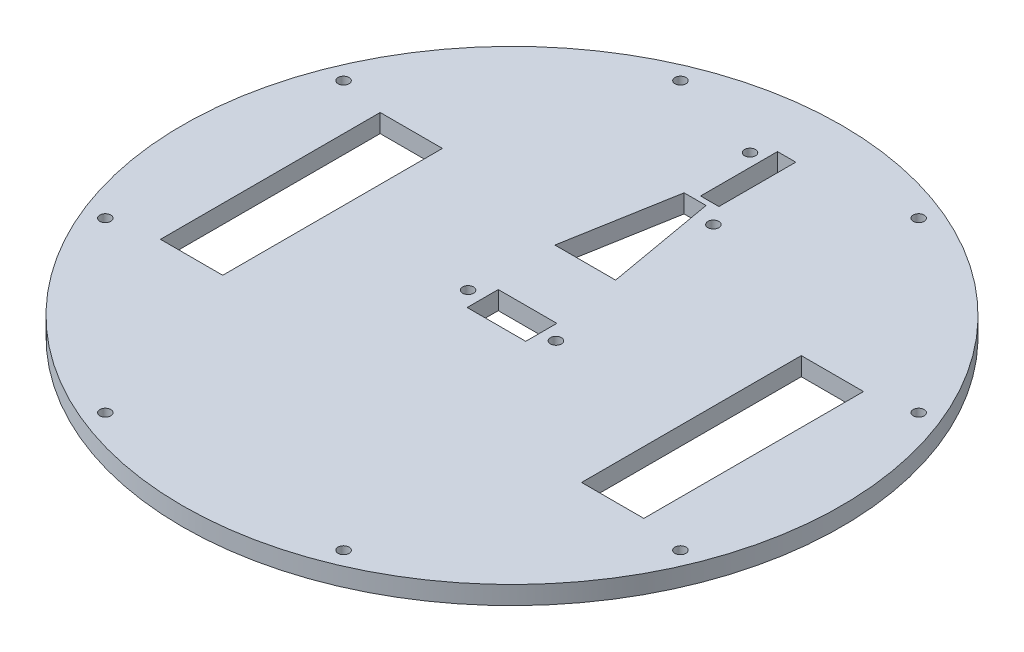
SolidWorks part; units mm, degrees
ref_plane "Front Plane" through (0, 0, 0) normal (0, 0, 1) x (1, 0, 0)
ref_plane "Top Plane" through (0, 0, 0) normal (0, 1, 0) x (1, 0, 0)
ref_plane "Right Plane" through (0, 0, 0) normal (1, 0, 0) x (0, 0, -1)
sketch "Sketch1" plane through (0, 0, 0) normal (0, 1, 0) x (1, 0, 0)
  line L0 (0, 96.8851) -> (0, -105.373) construction
  line L1 (-49, -30) -> (-66, -30)
  line L2 (-49, -30) -> (-49, 30)
  line L3 (-49, 30) -> (-66, 30)
  line L4 (-66, -30) -> (-66, 30)
  line L5 (-49, -30) -> (-66, 30) construction
  line L6 (-49, 30) -> (-66, -30) construction
  line L7 (49, 30) -> (66, -30) construction
  line L8 (49, -30) -> (66, 30) construction
  line L9 (66, -30) -> (66, 30)
  line L10 (49, 30) -> (66, 30)
  line L11 (49, -30) -> (49, 30)
  line L12 (49, -30) -> (66, -30)
  line L17 (10, 45) -> (-10, 45) construction
  line L23 (-2.5, 54) -> (2.5, 54)
  line L24 (10, 45) -> (10, 75) construction
  line L25 (10, 75) -> (-10, 75) construction
  line L26 (-10, 45) -> (-10, 75) construction
  line L27 (-2.5, 53.7585) -> (-2.5, 30.8093) construction
  line L32 (-2.5, 54) -> (-2.5, 75)
  line L33 (-2.5, 75) -> (2.5, 75)
  line L34 (-5.5, 52.5) -> (0.5, 52.5)
  line L35 (0.5, 52.5) -> (5.7898, 22.5)
  line L36 (5.7898, 22.5) -> (-10.7898, 22.5)
  line L37 (-5.5, 52.5) -> (-10.7898, 22.5)
  line L38 (2.5, 54) -> (2.5, 75)
  line L39 (-2.5, 54) -> (2.5, 75) construction
  line L40 (-2.5, 75) -> (2.5, 54) construction
  circle A0 centre (0, 0) radius 90
  circle A4 centre (-6, 71) radius 1.5
  circle A5 centre (6, 49) radius 1.5
  point P3 (-57.5, 0)
  point P14 (-90, 0)
  point P16 (0, -4.2439)
  point P17 (0, 75)
  point P20 (0, 64.5)
  point P28 (0, 90)
  point P51 (-2.5, 22.5)
  point P52 (-2.5, 52.5)
  dimension "D1" = 180
  dimension "D5" = 20
  dimension "D10" = 30
  dimension "D12" = 3
  dimension "D2" = 17
  dimension "D3" = 24
  dimension "D4" = 60
  dimension "D6" = 30
  dimension "D7" = 15
  dimension "D8" = 2.5
  dimension "D9" = 7.5
  dimension "D11" = 10
  dimension "D13" = 4
  dimension "D14" = 4
  dimension "D15" = 4
  dimension "D16" = 4
  dimension "D17" = 6
  dimension "D18" = 21
  dimension "D19" = 5
extrude "Boss-Extrude1" add sketch "Sketch1" along normal blind 5
sketch "Sketch3" plane through (0, 5, 0) normal (0, 1, 0) x (1, 0, 0)
  line L0 (0, 0) -> (32.5281, 78.5298) construction
  line L1 (66, 30) -> (49, 30) construction
  circle A0 centre (32.5281, 78.5298) radius 1.5
  circle A1 centre (0, 0) radius 85 construction
  circle A2 centre (0, 0) radius 90 construction
  circle A3 centre (78.5298, 32.5281) radius 1.5
  circle A4 centre (78.5298, -32.5281) radius 1.5
  circle A5 centre (32.5281, -78.5298) radius 1.5
  circle A6 centre (-32.5281, -78.5298) radius 1.5
  circle A7 centre (-78.5298, -32.5281) radius 1.5
  circle A8 centre (-78.5298, 32.5281) radius 1.5
  circle A9 centre (-32.5281, 78.5298) radius 1.5
  point P7 (0, 0)
  point P24 (0, 0)
  dimension "D1" = 3
  dimension "D2" = 5
  dimension "D4" = 67.5
  dimension "D3" = 8
extrude "Outer Screws" cut sketch "Sketch3" against normal blind 10
sketch "Sketch2" plane through (0, 5, 0) normal (0, 1, 0) x (1, 0, 0)
  line L0 (-8, -4.25) -> (8, -4.25)
  line L1 (-8, -4.25) -> (-8, 4.25)
  line L2 (-8, 4.25) -> (8, 4.25)
  line L3 (8, -4.25) -> (8, 4.25)
  line L4 (-8, -4.25) -> (8, 4.25) construction
  line L5 (-8, 4.25) -> (8, -4.25) construction
  circle A0 centre (-12, 0) radius 1.5
  circle A1 centre (12, 0) radius 1.5
  point P8 (0, 4.25)
  point P10 (8, 0)
  dimension "D3" = 3
  dimension "D1" = 16
  dimension "D2" = 8.5
  dimension "D4" = 12
  dimension "D5" = 12
extrude "Safety Link" cut sketch "Sketch2" against normal blind 10
